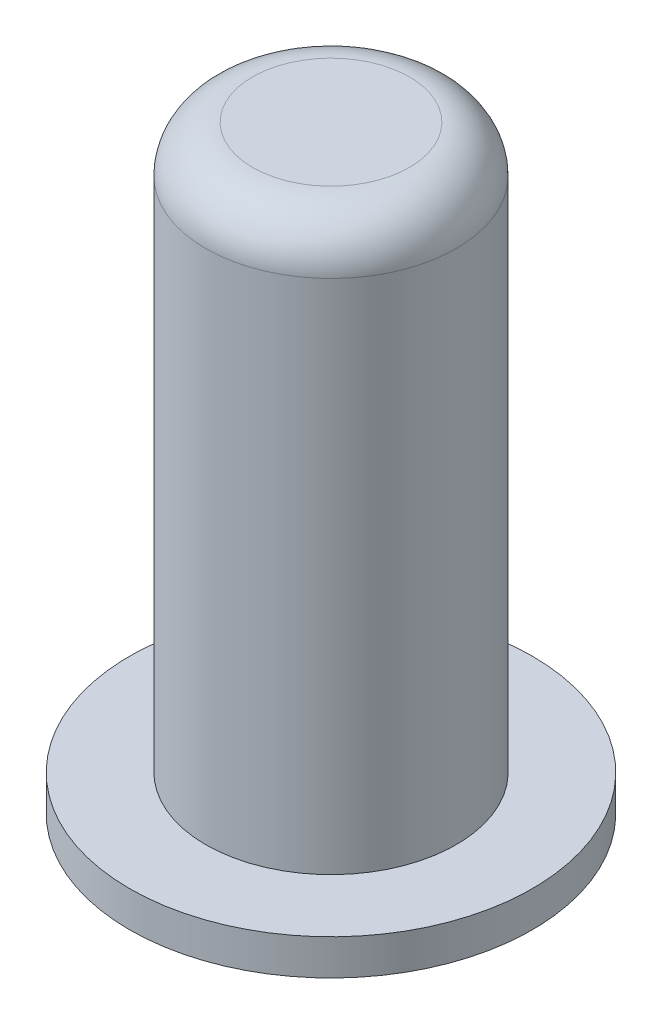
SolidWorks part; units mm, degrees
ref_plane "Front Plane" through (0, 0, 0) normal (0, 0, 1) x (1, 0, 0)
ref_plane "Top Plane" through (0, 0, 0) normal (0, 1, 0) x (1, 0, 0)
ref_plane "Right Plane" through (0, 0, 0) normal (1, 0, 0) x (0, 0, -1)
sketch "Sketch2" plane through (0, 0, 0) normal (0, 1, 0) x (1, 0, 0)
  circle A0 centre (0, 0) radius 5.4356
  dimension "D1" = 10.8712
extrude "Boss-Extrude1" add sketch "Sketch2" along normal blind 24.4348
sketch "Sketch3" plane through (0, 0, 0) normal (0, -1, 0) x (1, 0, 0)
  circle A0 centre (0, 0) radius 8.7376
  dimension "D1" = 17.4752
extrude "Boss-Extrude2" add sketch "Sketch3" along normal blind 1.5494
fillet "Fillet1" radius 2.032 1 edges at (0, 24.4348, 5.4356)
